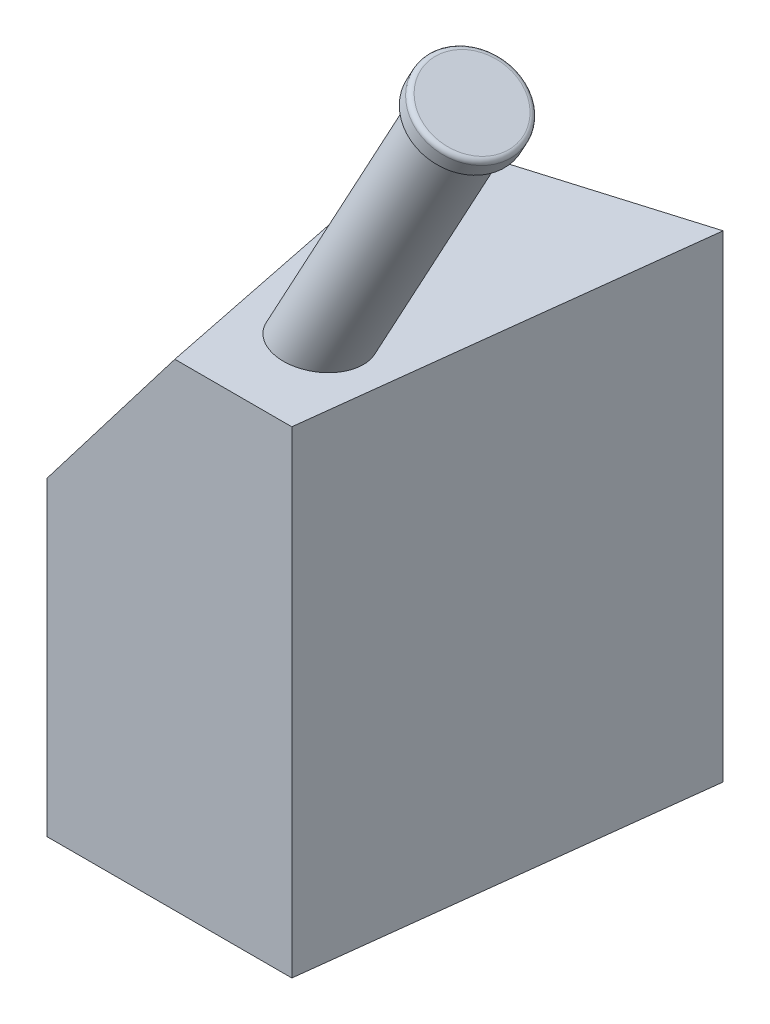
SolidWorks part; units mm, degrees
ref_plane "Front Plane" through (0, 0, 0) normal (0, 0, 1) x (1, 0, 0)
ref_plane "Top Plane" through (0, 0, 0) normal (0, 1, 0) x (1, 0, 0)
ref_plane "Right Plane" through (0, 0, 0) normal (1, 0, 0) x (0, 0, -1)
sketch "Sketch2" plane through (0, 0, 0) normal (0, 1, 0) x (1, 0, 0)
  line L0 (0, 0) -> (130.302, 0)
  line L1 (130.302, 0) -> (154.7294, 205.0521)
  line L2 (154.7294, 205.0521) -> (-52.1239, 143.2092)
  line L3 (-52.1239, 143.2092) -> (0, 0)
  dimension "D1" = 130.302
  dimension "D2" = 206.502
  dimension "D3" = 215.9
extrude "Boss-Extrude1" add sketch "Sketch2" along normal blind 254
ref_plane "Plane3" through (141.3327, 246.5263, 16.8366) normal (0.4965, 0.866, 0.0591) x (0.1183, 0, -0.993)
sketch "Sketch16" plane through (141.3327, 246.5263, 16.8366) normal (0.4965, 0.866, 0.0591) x (0.1183, 0, -0.993)
  circle A0 centre (59.5393, 48.3894) radius 20.3962
  dimension "D1" = 40.7924
extrude "Boss-Extrude2" add sketch "Sketch16" along normal blind 165.1 and the other way blind 50.8
sketch "Sketch17" plane through (223.3031, 389.5071, 26.6015) normal (0.4965, 0.866, 0.0591) x (0.868, -0.4953, -0.0338)
  circle A2 centre (-39.8244, 65.578) radius 25.4762
  circle A3 centre (-39.8244, 65.578) radius 25.4762
  dimension "D1" = 5.08
extrude "Boss-Extrude3" add sketch "Sketch17" against normal blind 10.16
fillet "Fillet1" radius 2.54 2 edges at (165.9949, 415.0472, -38.0778) (166.6321, 426.3726, -37.4768)
sketch "Sketch19" plane through (0, 0, 0) normal (0, 0, 1) x (1, 0, 0)
  line L0 (0, 254) -> (130.302, 254) construction
  line L1 (0, 254) -> (0, 0) construction
  point P0 (68.072, 254)
  point P1 (0, 165.1)
  dimension "D1" = 62.23
  dimension "D2" = 165.1
sketch "Sketch33" plane through (-43.5791, 0, -145.7638) normal (-0.2864, 0, -0.9581) x (-0.9581, 0, 0.2864)
  line L0 (8.9185, 254) -> (8.9185, 0) construction
  line L1 (-206.9815, 254) -> (8.9185, 254) construction
  point P0 (8.9185, 96.52)
  point P1 (-92.6815, 254)
  dimension "D1" = 114.3
  dimension "D2" = 96.52
ref_plane "Plane6" through (-74.2356, 46.7436, 4.635) normal (-0.845, 0.5321, 0.0528) x (0.0446, -0.0281, 0.9986)
sketch "Sketch35" plane through (-74.2356, 46.7436, 4.635) normal (-0.845, 0.5321, 0.0528) x (0.0446, -0.0281, 0.9986)
  line L0 (-177.1935, 239.0338) -> (49822.8065, 239.0338) construction
  point P3 (-117.5035, 239.0338)
  dimension "D1" = 59.69
sketch "Sketch37" plane through (-74.2356, 46.7436, 4.635) normal (-0.845, 0.5321, 0.0528) x (0.0446, -0.0281, 0.9986)
  line L0 (-177.1935, 239.0338) -> (-117.5035, 239.0338)
  line L1 (-117.5035, 239.0338) -> (-4.6414, 139.7108)
  line L2 (-4.6414, 139.7108) -> (-148.0503, 53.9036)
  line L3 (-148.0503, 53.9036) -> (-177.1935, 239.0338)
extrude "Cut-Extrude5" cut sketch "Sketch37" along normal through all
shell "Shell2" [suppressed] thickness 2.54
ref_plane "Plane8" through (-77.6744, 59.4764, 15.7733) normal (0.7838, -0.6002, -0.1592) x (-0.1264, 0.0968, -0.9873)
sketch "Sketch44" plane through (-77.6744, 59.4764, 15.7733) normal (0.7838, -0.6002, -0.1592) x (-0.1264, 0.0968, -0.9873)
  line L0 (129.9689, 229.1597) -> (15.977, 243.0534)
  line L1 (15.977, 243.0534) -> (15.977, 131.0847)
  line L2 (15.977, 131.0847) -> (129.9689, 229.1597)
extrude "Cut-Extrude14" cut sketch "Sketch44" against normal through all
sketch "Sketch46" plane through (0, 254, 0) normal (0, 1, 0) x (1, 0, 0)
  line L0 (45.2188, 172.3117) -> (45.2188, 112.5385)
  point P0 (45.2188, 112.5385)
sketch "Sketch54" plane through (48.3241, 47.921, 57.2723) normal (0.5433, 0.5388, 0.6439) x (0.8395, -0.3486, -0.4167)
  line L0 (-57.5596, 126.622) -> (-3.6988, 267.021)
  line L1 (-57.5596, 126.622) -> (-143.2464, 159.4938)
  line L2 (-3.6988, 267.021) -> (-89.3856, 299.8928)
  line L3 (-143.2464, 159.4938) -> (-89.3856, 299.8928)
extrude "Cut-Extrude16" cut sketch "Sketch54" against normal through all
sketch "Bend-Lines3" plane through (0, 0, 0) normal (0, 1, 0) x (1, 0, 0)
sketch "Bounding-Box3" plane through (0, 0, 0) normal (0, 1, 0) x (1, 0, 0)
